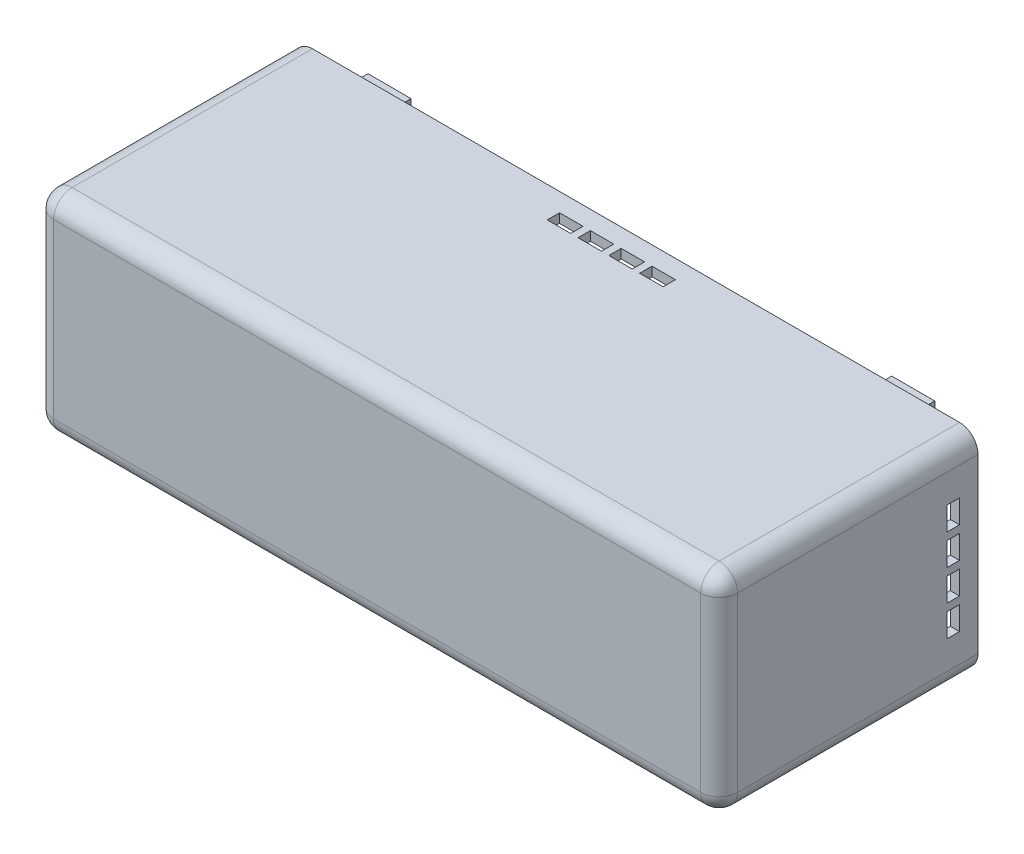
SolidWorks part; units mm, degrees
ref_plane "Front Plane" through (0, 0, 0) normal (0, 0, 1) x (1, 0, 0)
ref_plane "Top Plane" through (0, 0, 0) normal (0, 1, 0) x (1, 0, 0)
ref_plane "Right Plane" through (0, 0, 0) normal (1, 0, 0) x (0, 0, -1)
sketch "Sketch1" plane through (0, 0, 0) normal (0, 1, 0) x (1, 0, 0)
  line L1 (-96.7927, -59.5328) -> (-207.7927, -59.5328)
  line L2 (-96.7927, -59.5328) -> (-96.7927, -101.5328)
  line L3 (-96.7927, -101.5328) -> (-207.7927, -101.5328)
  line L4 (-207.7927, -59.5328) -> (-207.7927, -101.5328)
extrude "Boss-Extrude1" add sketch "Sketch1" along normal blind 34 contours L2 L1 L4 L3
fillet "Fillet1" radius 3 8 edges at (-207.7927, 17, 101.5328) (-152.2927, 34, 101.5328) (-96.7927, 17, 101.5328) (-152.2927, 0, 101.5328) (-207.7927, 0, 80.5328) (-207.7927, 34, 80.5328) (-96.7927, 0, 80.5328) (-96.7927, 34, 80.5328)
shell "Shell1" thickness 1.5
sketch "Sketch2" plane through (0, 0, 59.5328) normal (0, 0, -1) x (-1, 0, 0)
  line L0 (106.2927, 32.5) -> (106.2927, 31.5)
  line L2 (99.7927, 32.5) -> (204.7927, 32.5) construction
  line L3 (106.2927, 32.5) -> (113.2927, 32.5)
  line L4 (113.2927, 32.5) -> (113.2927, 31.5)
  line L5 (113.2927, 31.5) -> (106.2927, 31.5)
  line L7 (198.2927, 32.5) -> (191.2927, 32.5)
  line L8 (191.2927, 32.5) -> (191.2927, 31.5)
  line L9 (191.2927, 31.5) -> (198.2927, 31.5)
  line L10 (198.2927, 31.5) -> (198.2927, 32.5)
  line L11 (99.7927, 1.5) -> (204.7927, 1.5) construction
  line L12 (148.7927, 1.5) -> (155.7927, 1.5)
  line L13 (155.7927, 1.5) -> (155.7927, 2.5)
  line L14 (155.7927, 2.5) -> (148.7927, 2.5)
  line L15 (148.7927, 2.5) -> (148.7927, 1.5)
extrude "Boss-Extrude2" add sketch "Sketch2" along normal blind 2.5 separate body
sketch "Sketch3" plane through (0, 0, 57.0328) normal (0, 0, -1) x (-1, 0, 0)
  line L5 (191.2927, 31.5) -> (198.2927, 31.5)
  line L6 (191.2927, 31.5) -> (191.2927, 32.5)
  line L7 (191.2927, 32.5) -> (198.2927, 32.5)
  line L8 (113.2927, 32.5) -> (106.2927, 32.5)
  line L9 (106.2927, 32.5) -> (106.2927, 31.5)
  line L10 (106.2927, 31.5) -> (113.2927, 31.5)
  line L11 (113.2927, 31.5) -> (113.2927, 32.5)
  line L12 (113.2927, 32.5) -> (106.2927, 32.5)
  line L13 (106.2927, 32.5) -> (106.2927, 31.5)
  line L14 (106.2927, 31.5) -> (113.2927, 31.5)
  line L15 (113.2927, 31.5) -> (113.2927, 32.5)
  line L16 (198.2927, 31.5) -> (198.2927, 32.5)
  line L17 (148.7927, 2.5) -> (155.7927, 2.5)
  line L18 (148.7927, 2.5) -> (148.7927, 1.5)
  line L19 (148.7927, 1.5) -> (155.7927, 1.5)
  line L20 (155.7927, 2.5) -> (155.7927, 1.5)
  dimension "D1" = 0
extrude "Boss-Extrude3" add sketch "Sketch3" against normal blind 4.5
sketch "Sketch4" plane through (-113.2927, 0, 0) normal (-1, 0, 0) x (0, 0, 1)
  line L0 (61.5328, 31.5) -> (61.5328, 32.5)
  line L1 (61.5328, 32.5) -> (63.5328, 32.5)
  line L2 (63.5328, 32.5) -> (61.5328, 31.5)
extrude "Boss-Extrude4" add sketch "Sketch4" against normal blind 7
sketch "Sketch5" plane through (-191.2927, 0, 0) normal (1, 0, 0) x (0, 0, -1)
  line L0 (-61.5328, 31.5) -> (-61.5328, 32.5)
  line L1 (-61.5328, 32.5) -> (-63.5328, 32.5)
  line L2 (-63.5328, 32.5) -> (-61.5328, 31.5)
extrude "Boss-Extrude5" add sketch "Sketch5" against normal blind 7
sketch "Sketch6" plane through (-155.7927, 0, 0) normal (-1, 0, 0) x (0, 0, 1)
  line L0 (61.5328, 2.5) -> (61.5328, 1.5)
  line L1 (61.5328, 1.5) -> (63.5328, 1.5)
  line L2 (63.5328, 1.5) -> (61.5328, 2.5)
extrude "Boss-Extrude6" add sketch "Sketch6" against normal blind 7
sketch "Sketch7" plane through (0, 31.5, 0) normal (0, -1, 0) x (1, 0, 0)
  line L0 (-191.2927, 57.0328) -> (-198.2927, 57.0328)
  line L1 (-198.2927, 57.0328) -> (-198.2927, 58.5328)
  line L2 (-198.2927, 61.5328) -> (-198.2927, 57.0328) construction
  line L3 (-198.2927, 58.5328) -> (-191.2927, 58.5328)
  line L4 (-191.2927, 61.5328) -> (-191.2927, 57.0328) construction
  line L5 (-191.2927, 58.5328) -> (-191.2927, 57.0328)
  line L6 (-106.2927, 57.0328) -> (-113.2927, 57.0328)
  line L7 (-113.2927, 57.0328) -> (-113.2927, 58.5328)
  line L8 (-113.2927, 61.5328) -> (-113.2927, 57.0328) construction
  line L9 (-113.2927, 58.5328) -> (-106.2927, 58.5328)
  line L10 (-106.2927, 61.5328) -> (-106.2927, 57.0328) construction
  line L11 (-106.2927, 58.5328) -> (-106.2927, 57.0328)
extrude "Boss-Extrude7" add sketch "Sketch7" along normal blind 1
sketch "Sketch8" plane through (-198.2927, 0, 0) normal (-1, 0, 0) x (0, 0, 1)
  line L0 (57.0328, 31.5) -> (57.7828, 30.5)
  line L1 (57.0328, 30.5) -> (57.0328, 32.5) construction
  line L2 (58.5328, 30.5) -> (57.0328, 30.5) construction
  line L4 (58.2828, 30.5) -> (58.5328, 31.5)
  line L5 (58.5328, 31.5) -> (58.5328, 30.5)
  line L6 (58.5328, 30.5) -> (58.2828, 30.5)
  line L7 (57.0328, 31.5) -> (57.0328, 30.5)
  line L8 (57.0328, 30.5) -> (57.7828, 30.5)
extrude "Cut-Extrude1" cut sketch "Sketch8" against normal up to surface (92 mm away) up to face at (-106.2927, 31.6429, 59.39)
sketch "Sketch9" plane through (-155.7927, 0, 0) normal (-1, 0, 0) x (0, 0, 1)
  line L2 (57.0328, 2.5) -> (57.7828, 3.5)
  line L3 (57.7828, 3.5) -> (58.2828, 3.5)
  line L4 (58.2828, 3.5) -> (58.5328, 2.5)
  line L5 (61.5328, 2.5) -> (57.0328, 2.5) construction
  line L6 (58.5328, 2.5) -> (57.0328, 2.5)
extrude "Boss-Extrude8" add sketch "Sketch9" against normal blind 7
sketch "Sketch10" plane through (-96.7927, 0, 0) normal (1, 0, 0) x (0, 0, -1)
  line L0 (-59.5328, 17) -> (-62.5328, 17)
  line L1 (-62.5328, 17) -> (-64.5328, 17)
  line L2 (-59.5328, 31) -> (-59.5328, 3) construction
  line L3 (-62.5328, 17) -> (-62.5328, 7)
  line L4 (-62.5328, 7) -> (-64.5328, 7)
  line L5 (-64.5328, 7) -> (-64.5328, 27)
  line L6 (-64.5328, 27) -> (-62.5328, 27)
  line L7 (-62.5328, 27) -> (-62.5328, 17)
  line L8 (-62.5328, 22) -> (-64.5328, 22)
  line L9 (-62.5328, 12) -> (-64.5328, 12)
  line L10 (-62.5328, 22.6) -> (-64.5328, 22.6)
  line L11 (-62.5328, 17.6) -> (-64.5328, 17.6)
  line L12 (-62.5328, 12.6) -> (-64.5328, 12.6)
  line L13 (-62.5328, 7.6) -> (-64.5328, 7.6)
  line L14 (-64.5328, 26.4) -> (-62.5328, 26.4)
  line L15 (-62.5328, 21.4) -> (-64.5328, 21.4)
  line L16 (-62.5328, 16.4) -> (-64.5328, 16.4)
  line L17 (-62.5328, 11.4) -> (-64.5328, 11.4)
  line L18 (-62.5328, 6.4) -> (-64.5328, 6.4)
  line L19 (-64.5328, 27.6) -> (-62.5328, 27.6)
  dimension "D1" = 0.6
  dimension "D2" = 0.6
extrude "Cut-Extrude3" cut sketch "Sketch10" against normal up to surface (111 mm away) contours L14 L5 L10 L7 | L7 L15 L5 L11 | L3 L16 L5 L12 | L3 L17 L5 L13 up to face at (-207.7927, 17, 79.0328)
sketch "Sketch11" plane through (0, 34, 0) normal (0, 1, 0) x (1, 0, 0)
  line L0 (-152.2927, -59.5328) -> (-152.2927, -62.5328)
  line L1 (-99.7927, -59.5328) -> (-204.7927, -59.5328) construction
  line L2 (-152.2927, -62.5328) -> (-142.2927, -62.5328)
  line L3 (-142.2927, -62.5328) -> (-142.2927, -64.5328)
  line L4 (-142.2927, -64.5328) -> (-162.2927, -64.5328)
  line L5 (-162.2927, -64.5328) -> (-162.2927, -62.5328)
  line L6 (-162.2927, -62.5328) -> (-152.2927, -62.5328)
  line L7 (-157.2927, -62.5328) -> (-157.2927, -64.5328)
  line L8 (-152.2927, -62.5328) -> (-152.2927, -64.5328)
  line L9 (-147.2927, -62.5328) -> (-147.2927, -64.5328)
  line L10 (-157.8927, -62.5328) -> (-157.8927, -64.5328)
  line L11 (-161.6927, -64.5328) -> (-161.6927, -62.5328)
  line L12 (-152.8927, -62.5328) -> (-152.8927, -64.5328)
  line L13 (-147.8927, -62.5328) -> (-147.8927, -64.5328)
  line L14 (-142.8927, -62.5328) -> (-142.8927, -64.5328)
  line L15 (-156.6927, -62.5328) -> (-156.6927, -64.5328)
  line L16 (-162.8927, -64.5328) -> (-162.8927, -62.5328)
  line L17 (-151.6927, -62.5328) -> (-151.6927, -64.5328)
  line L18 (-146.6927, -62.5328) -> (-146.6927, -64.5328)
  line L19 (-141.6927, -62.5328) -> (-141.6927, -64.5328)
  dimension "D1" = 0.6
  dimension "D2" = 0.6
extrude "Cut-Extrude4" cut sketch "Sketch11" against normal up to surface (1.5 mm away) contours L11 L4 L10 L6 | L6 L15 L4 L12 | L2 L17 L4 L13 | L2 L18 L4 L14 up to face at (-152.2927, 32.5, 67.3661)
sketch "Sketch12" plane through (0, 0, 0) normal (0, -1, 0) x (1, 0, 0)
  line L1 (-99.7927, 59.5328) -> (-204.7927, 59.5328) construction
  line L2 (-126.0427, 59.5328) -> (-126.0427, 62.5328)
  line L3 (-126.0427, 62.5328) -> (-131.0427, 62.5328)
  line L4 (-131.0427, 62.5328) -> (-131.0427, 64.5328)
  line L5 (-131.0427, 64.5328) -> (-121.0427, 64.5328)
  line L6 (-121.0427, 64.5328) -> (-121.0427, 62.5328)
  line L7 (-121.0427, 62.5328) -> (-126.0427, 62.5328)
  line L10 (-125.4427, 62.5328) -> (-125.4427, 64.5328)
  line L11 (-121.6427, 64.5328) -> (-121.6427, 62.5328)
  line L12 (-126.6427, 62.5328) -> (-126.6427, 64.5328)
  line L14 (-130.4427, 62.5328) -> (-130.4427, 64.5328)
  line L16 (-174.1427, 62.5328) -> (-174.1427, 64.5328)
  line L17 (-177.9427, 62.5328) -> (-177.9427, 64.5328)
  line L18 (-179.1427, 62.5328) -> (-179.1427, 64.5328)
  line L19 (-182.9427, 64.5328) -> (-182.9427, 62.5328)
  line L20 (-183.5427, 62.5328) -> (-178.5427, 62.5328)
  line L21 (-183.5427, 64.5328) -> (-183.5427, 62.5328)
  line L22 (-173.5427, 64.5328) -> (-183.5427, 64.5328)
  line L23 (-173.5427, 62.5328) -> (-173.5427, 64.5328)
  line L24 (-178.5427, 62.5328) -> (-173.5427, 62.5328)
  dimension "D1" = 0.6
  dimension "D3" = 0.6
extrude "Cut-Extrude5" cut sketch "Sketch12" against normal up to surface (1.5 mm away) contours L11 L5 L10 L7 | L14 L3 L12 L5 | L17 L24 L16 L22 | L18 L22 L19 L20 up to face at (-152.2927, 1.5, 70.2828)
